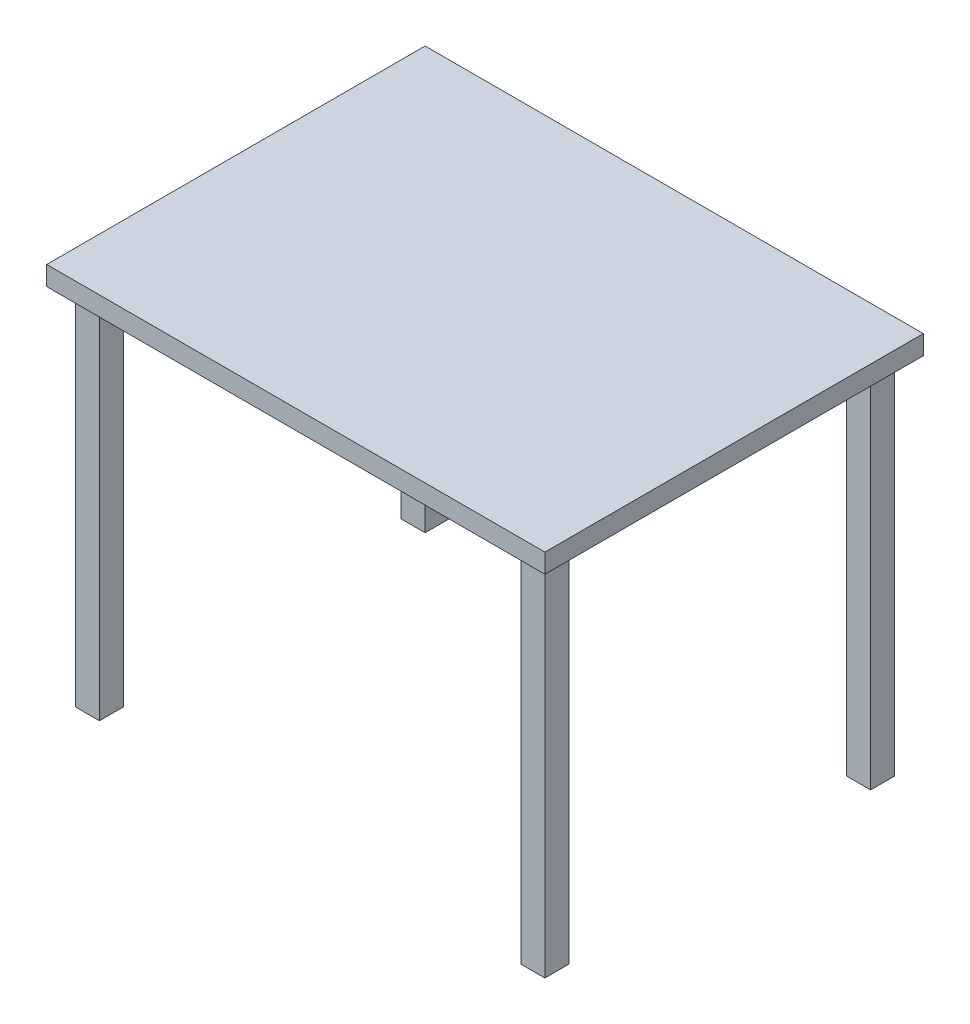
SolidWorks part; units mm, degrees
ref_plane "Front Plane" through (0, 0, 0) normal (0, 0, 1) x (1, 0, 0)
ref_plane "Top Plane" through (0, 0, 0) normal (0, 1, 0) x (1, 0, 0)
ref_plane "Right Plane" through (0, 0, 0) normal (1, 0, 0) x (0, 0, -1)
sketch "Sketch1" plane through (0, 0, 0) normal (0, 1, 0) x (1, 0, 0)
  line L1 (-520, -395) -> (520, -395)
  line L2 (-520, -395) -> (-520, 395)
  line L3 (-520, 395) -> (520, 395)
  line L4 (520, -395) -> (520, 395)
  line L5 (-520, -395) -> (520, 395) construction
  line L6 (-520, 395) -> (520, -395) construction
  point P0 (0, 0)
  dimension "D1" = 1040
  dimension "D2" = 790
extrude "Boss-Extrude1" add sketch "Sketch1" along normal mid plane 40
sketch "Sketch2" plane through (0, -20, 0) normal (0, -1, 0) x (1, 0, 0)
  line L5 (-520, 395) -> (520, 395) construction
  line L6 (-490, 365) -> (-440, 365)
  line L7 (-490, 365) -> (-490, 315)
  line L8 (-490, 315) -> (-440, 315)
  line L9 (-440, 365) -> (-440, 315)
  line L10 (-520, -395) -> (-520, 395) construction
  line L11 (0, 0) -> (0, 50000) construction
  line L12 (0, 0) -> (50000, 0) construction
  line L13 (-490, -315) -> (-440, -315)
  line L14 (-440, -365) -> (-440, -315)
  line L15 (-490, -365) -> (-440, -365)
  line L16 (-490, -365) -> (-490, -315)
  line L17 (490, -365) -> (490, -315)
  line L18 (490, -365) -> (440, -365)
  line L19 (440, -365) -> (440, -315)
  line L20 (490, -315) -> (440, -315)
  line L21 (490, 315) -> (440, 315)
  line L22 (440, 365) -> (440, 315)
  line L23 (490, 365) -> (440, 365)
  line L24 (490, 365) -> (490, 315)
  dimension "D1" = 50
  dimension "D2" = 30
  dimension "D3" = 30
extrude "Boss-Extrude2" add sketch "Sketch2" along normal blind 760
